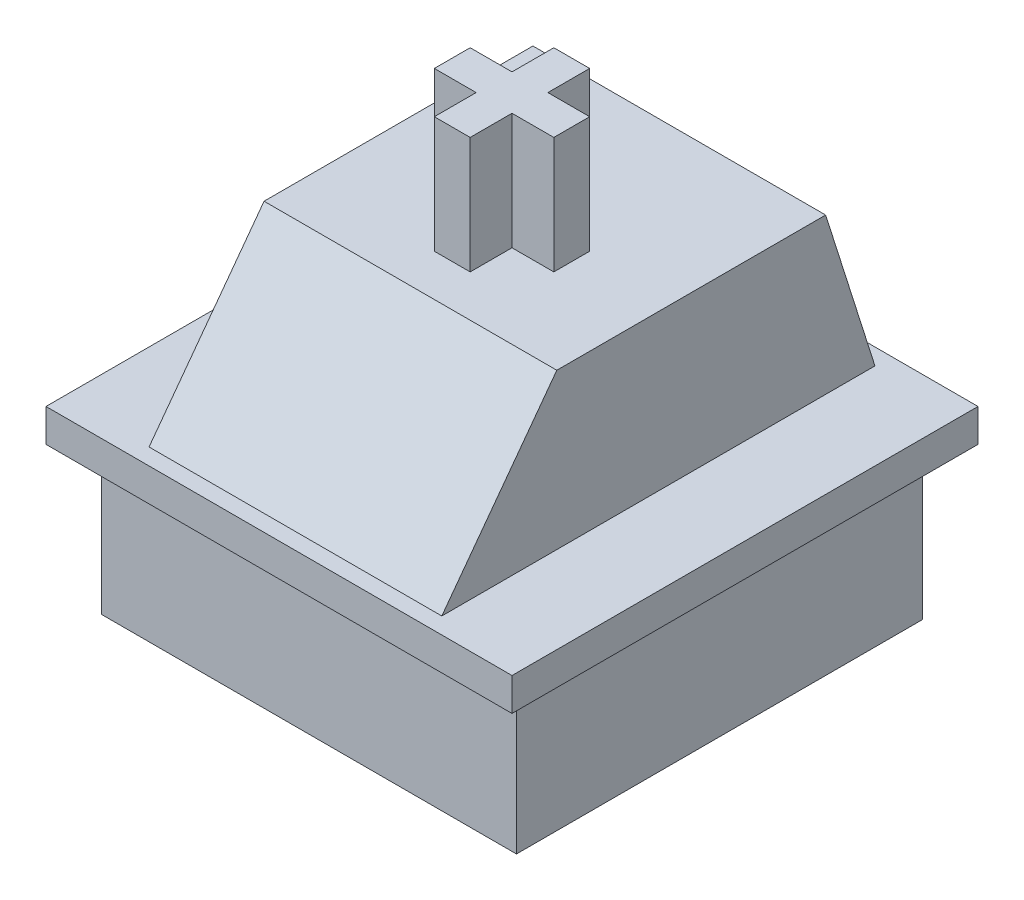
SolidWorks part; units mm, degrees
ref_plane "前视基准面" through (0, 0, 0) normal (0, 0, 1) x (1, 0, 0)
ref_plane "上视基准面" through (0, 0, 0) normal (0, 1, 0) x (1, 0, 0)
ref_plane "右视基准面" through (0, 0, 0) normal (1, 0, 0) x (0, 0, -1)
other "Configuration Table"
sketch "草图4" plane through (0, 0, 0) normal (0, 1, 0) x (1, 0, 0)
  line L1 (-7.8, -7.8) -> (7.8, -7.8)
  line L2 (-7.8, -7.8) -> (-7.8, 7.8)
  line L3 (-7.8, 7.8) -> (7.8, 7.8)
  line L4 (7.8, -7.8) -> (7.8, 7.8)
  line L5 (-7.8, -7.8) -> (7.8, 7.8) construction
  line L6 (-7.8, 7.8) -> (7.8, -7.8) construction
  point P0 (0, 0)
  dimension "D1" = 15.6
extrude "凸台-拉伸1" add sketch "草图4" along normal blind 1.1
sketch "草图5" plane through (0, 0, 0) normal (1, 0, 0) x (0, 0, -1)
  line L0 (-7.8, 1.1) -> (7.8, 1.1) construction
  line L1 (-7.25, 1.1) -> (7.25, 1.1)
  line L2 (-7.25, 1.1) -> (-3.4, 6.3)
  line L3 (-3.4, 6.3) -> (5.6, 6.3)
  line L4 (7.25, 1.1) -> (5.6, 6.3)
  line L5 (-7.25, 1.1) -> (-7.8, 1.1)
  line L6 (7.8, 1.1) -> (7.25, 1.1)
  line L7 (7.8, 1.1) -> (7.8, 0) construction
  dimension "D1" = 14.5
  dimension "D2" = 5.2
  dimension "D3" = 11.2
  dimension "D4" = 9
extrude "凸台-拉伸2" add sketch "草图5" along normal mid plane 9.8 contours L1 L4 L3 L2
sketch "草图7" plane through (0, 0, 0) normal (0, -1, 0) x (1, 0, 0)
  line L1 (-6.95, -6.8) -> (6.95, -6.8)
  line L2 (-6.95, -6.8) -> (-6.95, 6.8)
  line L3 (-6.95, 6.8) -> (6.95, 6.8)
  line L4 (6.95, -6.8) -> (6.95, 6.8)
  line L5 (-6.95, -6.8) -> (6.95, 6.8) construction
  line L6 (-6.95, 6.8) -> (6.95, -6.8) construction
  point P0 (0, 0)
  dimension "D1" = 13.9
  dimension "D2" = 13.6
extrude "凸台-拉伸4" add sketch "草图7" along normal blind 5
sketch "草图6" plane through (0, -5, 0) normal (0, -1, 0) x (1, 0, 0)
  circle A0 centre (0, 0) radius 1.95
  dimension "D1" = 3.9
extrude "凸台-拉伸3" add sketch "草图6" along normal blind 3.3
sketch "草图8" plane through (0, 6.3, 0) normal (0, 1, 0) x (1, 0, 0)
  line L1 (-0.6, -2) -> (0.6, -2)
  line L2 (-0.6, -2) -> (-0.6, 2)
  line L3 (-0.6, 2) -> (0.6, 2)
  line L4 (0.6, -2) -> (0.6, 2)
  line L5 (-0.6, -2) -> (0.6, 2) construction
  line L6 (-0.6, 2) -> (0.6, -2) construction
  line L7 (-2, -0.6) -> (2, -0.6)
  line L8 (-2, -0.6) -> (-2, 0.6)
  line L9 (-2, 0.6) -> (2, 0.6)
  line L10 (2, -0.6) -> (2, 0.6)
  line L11 (-2, -0.6) -> (2, 0.6) construction
  line L12 (-2, 0.6) -> (2, -0.6) construction
  point P0 (0, 0)
  point P6 (0, 0)
  dimension "D1" = 1.2
  dimension "D2" = 4
extrude "凸台-拉伸5" add sketch "草图8" along normal blind 3.9 contours L3 L4 L1 L2 | L9 L10 L7 L8
sketch "草图9" plane through (0, -5, 0) normal (0, -1, 0) x (1, 0, 0)
  line L1 (2.04, -4.86) -> (3.04, -4.86)
  line L2 (2.04, -4.86) -> (2.04, -5.16)
  line L3 (2.04, -5.16) -> (3.04, -5.16)
  line L4 (3.04, -4.86) -> (3.04, -5.16)
  line L5 (2.04, -4.86) -> (3.04, -5.16) construction
  line L6 (2.04, -5.16) -> (3.04, -4.86) construction
  line L7 (-4.31, -2.39) -> (-3.31, -2.39)
  line L8 (-4.31, -2.39) -> (-4.31, -2.69)
  line L9 (-4.31, -2.69) -> (-3.31, -2.69)
  line L10 (-3.31, -2.39) -> (-3.31, -2.69)
  line L11 (-4.31, -2.39) -> (-3.31, -2.69) construction
  line L12 (-4.31, -2.69) -> (-3.31, -2.39) construction
  point P0 (2.54, -5.01)
  point P5 (-3.81, -2.54)
  dimension "D1" = 2.54
  dimension "D2" = 3.81
  dimension "D3" = 2.54
  dimension "D4" = 5.01
  dimension "D5" = 1
  dimension "D6" = 0.3
extrude "凸台-拉伸6" add sketch "草图9" along normal blind 3.8
